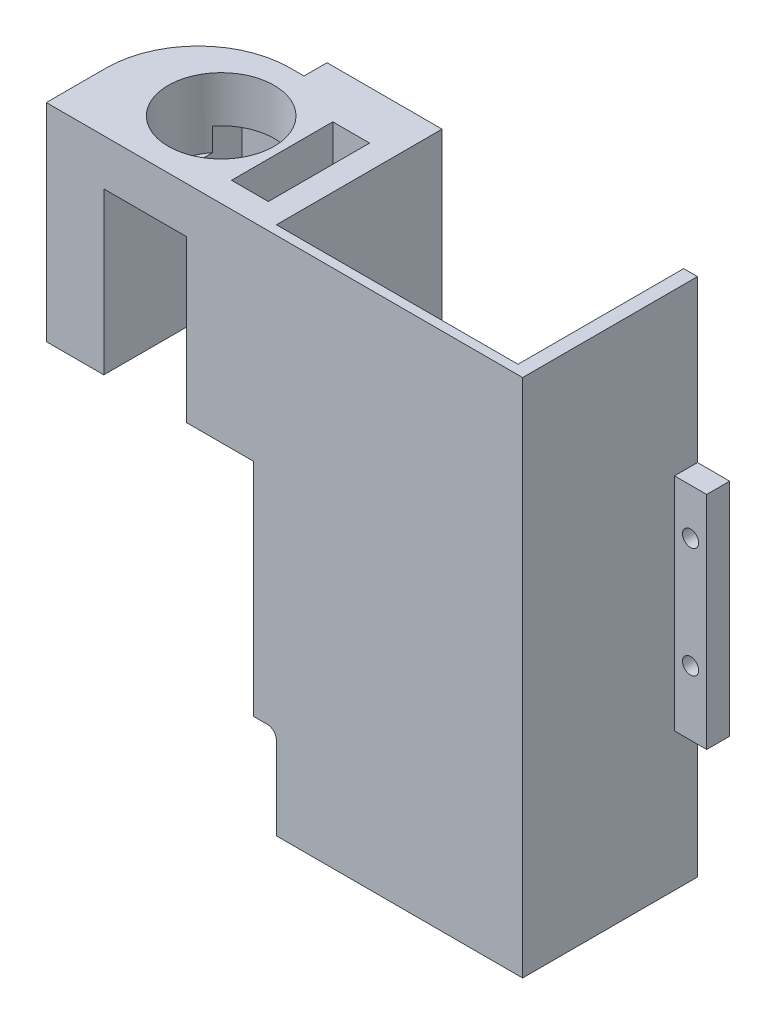
SolidWorks part; units mm, degrees
material "黄铜"
ref_plane "前视基准面" through (0, 0, 0) normal (0, 0, 1) x (1, 0, 0)
ref_plane "上视基准面" through (0, 0, 0) normal (0, 1, 0) x (1, 0, 0)
ref_plane "右视基准面" through (0, 0, 0) normal (1, 0, 0) x (0, 0, -1)
sketch "草图1" plane through (0, 0, 0) normal (0, 1, 0) x (1, 0, 0)
  line L1 (0, 0) -> (58.5, 0)
  line L2 (0, 0) -> (0, 42)
  line L3 (0, 42) -> (58.5, 42)
  line L4 (58.5, 0) -> (58.5, 42)
  dimension "D1" = 42
  dimension "D2" = 58.5
extrude "凸台-拉伸1" add sketch "草图1" along normal blind 123
sketch "草图2" plane through (0, 123, 0) normal (0, 1, 0) x (1, 0, 0)
  line L0 (0, 0) -> (58.5, 42)
  line L2 (3, 3) -> (55.5, 3)
  line L3 (3, 3) -> (3, 39)
  line L4 (3, 39) -> (55.5, 39)
  line L5 (55.5, 3) -> (55.5, 39)
  line L6 (3, 3) -> (55.5, 39) construction
  line L7 (3, 39) -> (55.5, 3) construction
  point P4 (29.25, 21)
  dimension "D1" = 36
  dimension "D2" = 52.5
extrude "切除-拉伸1" cut sketch "草图2" against normal blind 120 contours L4 L3 L2 L0 | L2 L5 L4 L0
sketch "草图3" plane through (0, 0, -42) normal (0, 0, -1) x (-1, 0, 0)
  line L1 (-58.5, 0) -> (0, 0)
  line L2 (-58.5, 0) -> (-58.5, 123)
  line L3 (-58.5, 123) -> (0, 123)
  line L4 (0, 0) -> (0, 123)
extrude "切除-拉伸2" cut sketch "草图3" against normal blind 4
sketch "草图4" plane through (0, 0, -3) normal (0, 0, -1) x (-1, 0, 0)
  line L1 (-55.5, 3) -> (-3, 3)
  line L2 (-55.5, 3) -> (-55.5, 123)
  line L3 (-55.5, 123) -> (-3, 123)
  line L4 (-3, 3) -> (-3, 123)
extrude "切除-拉伸3" cut sketch "草图4" against normal blind 1
sketch "草图5" plane through (0, 123, 0) normal (0, 1, 0) x (1, 0, 0)
  line L1 (0, 0) -> (58.5, 0)
  line L2 (0, 0) -> (0, 38)
  line L3 (0, 38) -> (58.5, 38)
  line L4 (58.5, 0) -> (58.5, 38)
extrude "切除-拉伸4" cut sketch "草图5" against normal blind 10
sketch "草图6" plane through (0, 0, -38) normal (0, 0, -1) x (-1, 0, 0)
  line L1 (0, 113) -> (7, 113)
  line L2 (0, 113) -> (0, 0)
  line L3 (0, 0) -> (7, 0)
  line L4 (7, 113) -> (7, 0)
  dimension "D1" = 7
  dimension "D2" = 113
extrude "凸台-拉伸2" add sketch "草图6" against normal blind 5
sketch "草图7" plane through (0, 0, -33) normal (0, 0, 1) x (1, 0, 0)
  line L0 (-3.5, 113) -> (-3.5, 0)
  line L1 (-7, 113) -> (0, 113) construction
  line L2 (0, 0) -> (-7, 0) construction
  point P6 (-3.5, 40.5)
  point P7 (-3.5, 73)
  point P8 (-3.5, 8)
  dimension "D1" = 8
  dimension "D2" = 40
  dimension "D3" = 32.5
sketch "草图10" plane through (0, 0, 0) normal (0, 0, 1) x (1, 0, 0)
  line L1 (0, 0) -> (3, 0)
  line L2 (0, 0) -> (0, 20)
  line L3 (0, 20) -> (3, 20)
  line L4 (3, 0) -> (3, 20)
  dimension "D1" = 3
  dimension "D2" = 20
extrude "切除-拉伸5" cut sketch "草图10" against normal up to surface (33 mm away) up to face at (-3.5, 56.5, -33)
sketch "草图11" plane through (0, 0, -33) normal (0, 0, 1) x (1, 0, 0)
  line L0 (-3.5, 113) -> (-3.5, 0) construction
  point P0 (-3.5, 73)
  point P3 (-3.5, 56.5)
  point P7 (-3.5, 8)
  point P11 (-3.5, 40.5)
hole_wizard "孔2" positions "草图11" profile "草图12" legacy
sketch "草图12" plane through (-3.5, 40.5, -33) normal (1, 0, 0) x (0, -1, 0)
  line L0 (0, 0) -> (0, 5)
  line L1 (0, 5) -> (1.75, 5)
  line L2 (1.75, 5) -> (1.75, 0)
  line L3 (1.75, 0) -> (0, 0)
  line L4 (0, 110) -> (0, -10) construction
  dimension "直径" = 3.5
  dimension "深度" = 5
sketch "草图13" plane through (0, 0, -38) normal (0, 0, -1) x (-1, 0, 0)
  line L1 (-58.5, 113) -> (-65.5, 113)
  line L2 (-58.5, 113) -> (-58.5, 0)
  line L3 (-58.5, 0) -> (-65.5, 0)
  line L4 (-65.5, 113) -> (-65.5, 0)
  dimension "D1" = 7
  dimension "D2" = 113
extrude "凸台-拉伸3" add sketch "草图13" against normal blind 5
sketch "草图14" plane through (0, 0, -33) normal (0, 0, 1) x (1, 0, 0)
  line L0 (62, 113) -> (62, 68)
  line L1 (58.5, 113) -> (65.5, 113) construction
  line L2 (62, 68) -> (62, 44)
  dimension "D1" = 45
  dimension "D2" = 24
sketch "草图15" plane through (0, 0, -33) normal (0, 0, 1) x (1, 0, 0)
  point P0 (62, 68)
  point P3 (62, 44)
hole_wizard "孔3" positions "草图15" profile "草图16" legacy end condition through all
sketch "草图16" plane through (62, 68, -33) normal (1, 0, 0) x (0, -1, 0)
  line L0 (0, 0) -> (0, 5)
  line L1 (0, 5) -> (1.75, 5)
  line L2 (1.75, 5) -> (1.75, 0)
  line L3 (1.75, 0) -> (0, 0)
  line L4 (0, 110) -> (0, -10) construction
  dimension "直径" = 3.5
  dimension "深度" = 5
sketch "草图17" plane through (0, 0, -33) normal (0, 0, 1) x (1, 0, 0)
  line L0 (65.5, 113) -> (65.5, 0) construction
  line L1 (58.5, 113) -> (65.5, 113)
  line L2 (58.5, 113) -> (58.5, 78)
  line L3 (58.5, 78) -> (65.5, 78)
  line L4 (65.5, 113) -> (65.5, 78)
  line L5 (58.5, 113) -> (58.5, 0) construction
  line L6 (65.5, 0) -> (58.5, 0)
  line L7 (65.5, 0) -> (65.5, 30)
  line L8 (65.5, 30) -> (58.5, 30)
  line L9 (58.5, 0) -> (58.5, 30)
  dimension "D1" = 30
  dimension "D2" = 35
extrude "切除-拉伸6" cut sketch "草图17" against normal blind 5 contours L2 L1 L4 L3 | L7 L6 L9 L8
sketch "草图18" plane through (0, 0, -33) normal (0, 0, 1) x (1, 0, 0)
  line L1 (0, 20) -> (3, 20)
  line L2 (0, 20) -> (0, 0)
  line L3 (0, 0) -> (3, 0)
  line L4 (3, 20) -> (3, 0)
extrude "凸台-拉伸4" add sketch "草图18" along normal blind 5
sketch "草图19" plane through (3, 0, 0) normal (-1, 0, 0) x (0, 0, 1)
  line L1 (-28, 0) -> (0, 0)
  line L2 (-28, 0) -> (-28, 20)
  line L3 (-28, 20) -> (0, 20)
  line L4 (0, 0) -> (0, 20)
extrude "切除-拉伸7" cut sketch "草图19" against normal blind 2
fillet "圆角3" radius 2 1 edges at (5, 20, -1)
sketch "草图21" plane through (0, 0, 0) normal (-1, 0, 0) x (0, 0, 1)
  line L0 (0, 113) -> (0, 20) construction
  line L1 (-33, 113) -> (0, 113)
  line L2 (-33, 113) -> (-33, 83)
  line L3 (-33, 83) -> (0, 83)
  line L4 (0, 113) -> (0, 83)
  dimension "D1" = 30
extrude "凸台-拉伸6" add sketch "草图21" along normal blind 30
sketch "草图22" plane through (0, 113, 0) normal (0, 1, 0) x (1, 0, 0)
  line L1 (-45, 0) -> (-30, 0)
  line L2 (-30, 0) -> (-30, 33)
  line L3 (-45, 0) -> (-45, 33)
  line L4 (-45, 33) -> (-30, 33)
  dimension "D1" = 15
extrude "凸台-拉伸7" add sketch "草图22" against normal blind 30
sketch "草图23" plane through (0, 113, 0) normal (0, 1, 0) x (1, 0, 0)
  line L0 (-45, 0) -> (58.5, 0) construction
  line L1 (-7, 33) -> (-40, 33)
  line L2 (-7, 33) -> (-7, 0)
  line L3 (-7, 0) -> (-40, 0)
  line L4 (-40, 33) -> (-40, 0)
  line L5 (-40, 0) -> (-7, 33)
  dimension "D1" = 33
sketch "草图24" plane through (0, 0, 0) normal (0, 0, 1) x (1, 0, 0)
  line L0 (-40, 113) -> (-7, 113) construction
  line L1 (-7, 113) -> (-40, 113)
  line L2 (-7, 113) -> (-7, 103)
  line L3 (-7, 103) -> (-40, 103)
  line L4 (-40, 113) -> (-40, 103)
  line L5 (-3.5, 113) -> (-3.5, 0) construction
  line L6 (-45, 83) -> (0, 83) construction
  line L7 (-32.5, 103) -> (-14.5, 103)
  line L8 (-32.5, 103) -> (-32.5, 83)
  line L9 (-32.5, 83) -> (-14.5, 83)
  line L10 (-14.5, 103) -> (-14.5, 83)
  line M16 (-45, 83) -> (0, 83)
  dimension "D1" = 10
  dimension "D2" = 3.5
  dimension "D3" = 33
  dimension "D4" = 18
  dimension "D5" = 7.5
extrude "切除-拉伸8" cut sketch "草图24" against normal blind 30 contours L10 L3 L8 M16
sketch "草图25" plane through (0, 113, 0) normal (0, 1, 0) x (1, 0, 0)
  line L0 (-40, 0) -> (-7, 33) construction
  point P0 (-23.5, 16.5)
hole_wizard "孔4" positions "草图25" profile "草图26" legacy
sketch "草图26" plane through (-23.5, 113, -16.5) normal (1, 0, 0) x (0, 0, 1)
  line L0 (0, 0) -> (0, 15)
  line L1 (0, 15) -> (11.5, 15)
  line L2 (11.5, 15) -> (11.5, 0)
  line L3 (11.5, 0) -> (0, 0)
  line L4 (0, 110) -> (0, -10) construction
  dimension "直径" = 23
  dimension "深度" = 15
sketch "草图27" plane through (0, 0, -33) normal (0, 0, -1) x (-1, 0, 0)
  line L1 (7, 113) -> (22, 113)
  line L2 (7, 113) -> (7, 53)
  line L3 (7, 53) -> (22, 53)
  line L4 (22, 113) -> (22, 53)
  dimension "D1" = 60
  dimension "D2" = 15
extrude "凸台-拉伸8" add sketch "草图27" along normal blind 5
sketch "草图28" plane through (0, 83, 0) normal (0, -1, 0) x (-1, 0, 0)
  line L0 (45, 33) -> (45, 0) construction
  line L1 (0, 33) -> (45, 33)
  line L2 (0, 33) -> (0, 30)
  line L3 (0, 30) -> (45, 30)
  line L4 (45, 33) -> (45, 30)
  dimension "D1" = 3
extrude "凸台-拉伸9" add sketch "草图28" along normal blind 15
sketch "草图29" plane through (0, 83, 0) normal (0, -1, 0) x (1, 0, 0)
  line L1 (-14.5, 0) -> (0, 0)
  line L2 (-14.5, 0) -> (-14.5, -30)
  line L3 (-14.5, -30) -> (0, -30)
  line L4 (0, 0) -> (0, -30)
  line L5 (-45, 0) -> (-32.5, 0)
  line L6 (-45, 0) -> (-45, -30)
  line L7 (-45, -30) -> (-32.5, -30)
  line L8 (-32.5, 0) -> (-32.5, -30)
extrude "凸台-拉伸10" add sketch "草图29" along normal blind 15
fillet "圆角6" radius 20 1 edges at (-45, 90.5, -33)
sketch "草图30" plane through (0, 68, 0) normal (0, -1, 0) x (1, 0, 0)
  line L0 (0, -33) -> (-14.5, 0)
  line L2 (-10.25, -5.5) -> (-4.25, -5.5)
  line L3 (-10.25, -5.5) -> (-10.25, -27.5)
  line L4 (-10.25, -27.5) -> (-4.25, -27.5)
  line L5 (-4.25, -5.5) -> (-4.25, -27.5)
  line L6 (-10.25, -5.5) -> (-4.25, -27.5) construction
  line L7 (-10.25, -27.5) -> (-4.25, -5.5) construction
  line L8 (-4.25, -5.5) -> (-2.25, -5.5)
  line L9 (-4.25, -5.5) -> (-4.25, -27.5)
  line L10 (-4.25, -27.5) -> (-2.25, -27.5)
  line L11 (-2.25, -5.5) -> (-2.25, -27.5)
  point P4 (-7.25, -16.5)
  dimension "D1" = 6
  dimension "D2" = 22
  dimension "D3" = 2
extrude "切除-拉伸9" cut sketch "草图30" against normal through all contours L5 L2 L3 L0 | L5 L0 L3 L4 | L9 L8 L11 L10
